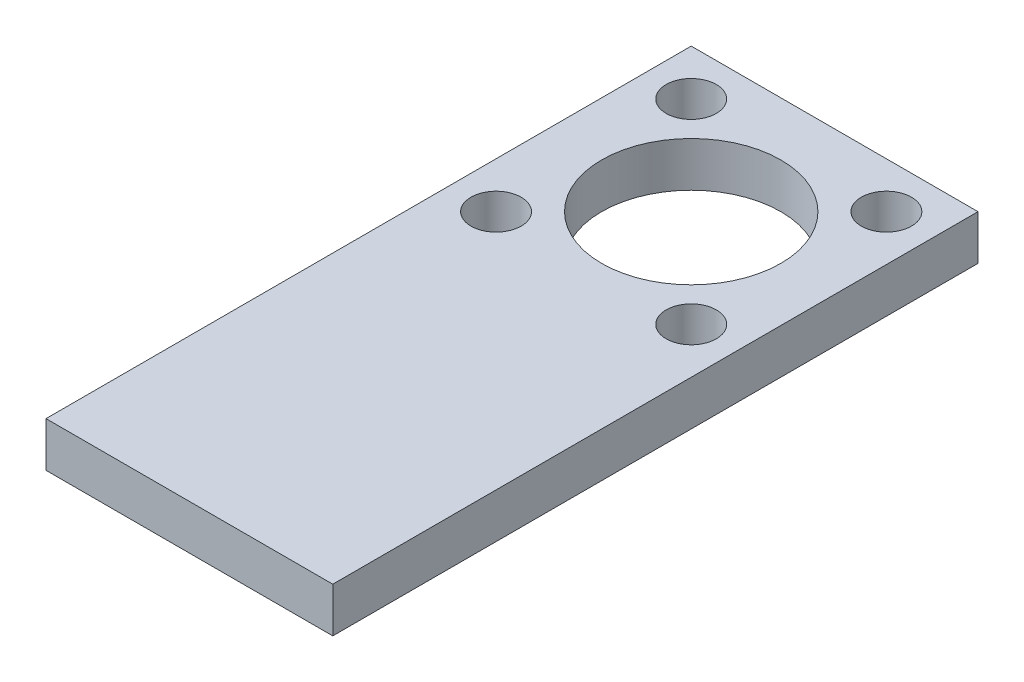
SolidWorks part; units mm, degrees
ref_plane "Front Plane" through (0, 0, 0) normal (0, 0, 1) x (1, 0, 0)
ref_plane "Top Plane" through (0, 0, 0) normal (0, 1, 0) x (1, 0, 0)
ref_plane "Right Plane" through (0, 0, 0) normal (1, 0, 0) x (0, 0, -1)
sketch "Sketch2" plane through (0, 0, 0) normal (0, 1, 0) x (1, 0, 0)
  line L1 (0, 0) -> (-20.32, 0)
  line L2 (0, 0) -> (0, -45.72)
  line L3 (0, -45.72) -> (-20.32, -45.72)
  line L4 (-20.32, 0) -> (-20.32, -45.72)
  line L5 (-10.16, -20.32) -> (-20.32, -20.32) construction
  line L6 (-10.16, -20.32) -> (0, -20.32) construction
  dimension "D1" = 45.72
  dimension "D2" = 20.32
extrude "Boss-Extrude4" add sketch "Sketch2" along normal blind 3.175
sketch "Sketch7" plane through (0, 3.175, 0) normal (0, 1, 0) x (1, 0, 0)
  line L0 (-10.16, 0) -> (-10.16, -20.32) construction
  line L1 (0, 0) -> (-20.32, 0) construction
  line L2 (-10.16, -10.16) -> (-3.2452, -17.0748) construction
  line L3 (-10.16, -10.16) -> (-17.0748, -17.0748) construction
  line L4 (-10.16, -10.16) -> (-17.0748, -3.2452) construction
  line L5 (-10.16, -10.16) -> (-3.2452, -3.2452) construction
  circle A0 centre (-17.0748, -17.0748) radius 1.778
  circle A1 centre (-3.2452, -17.0748) radius 1.778
  circle A2 centre (-17.0748, -3.2452) radius 1.778
  circle A3 centre (-3.2452, -3.2452) radius 1.778
  circle A4 centre (-10.16, -10.16) radius 6.35
extrude "Cut-Extrude1" cut sketch "Sketch7" against normal blind 3.175
